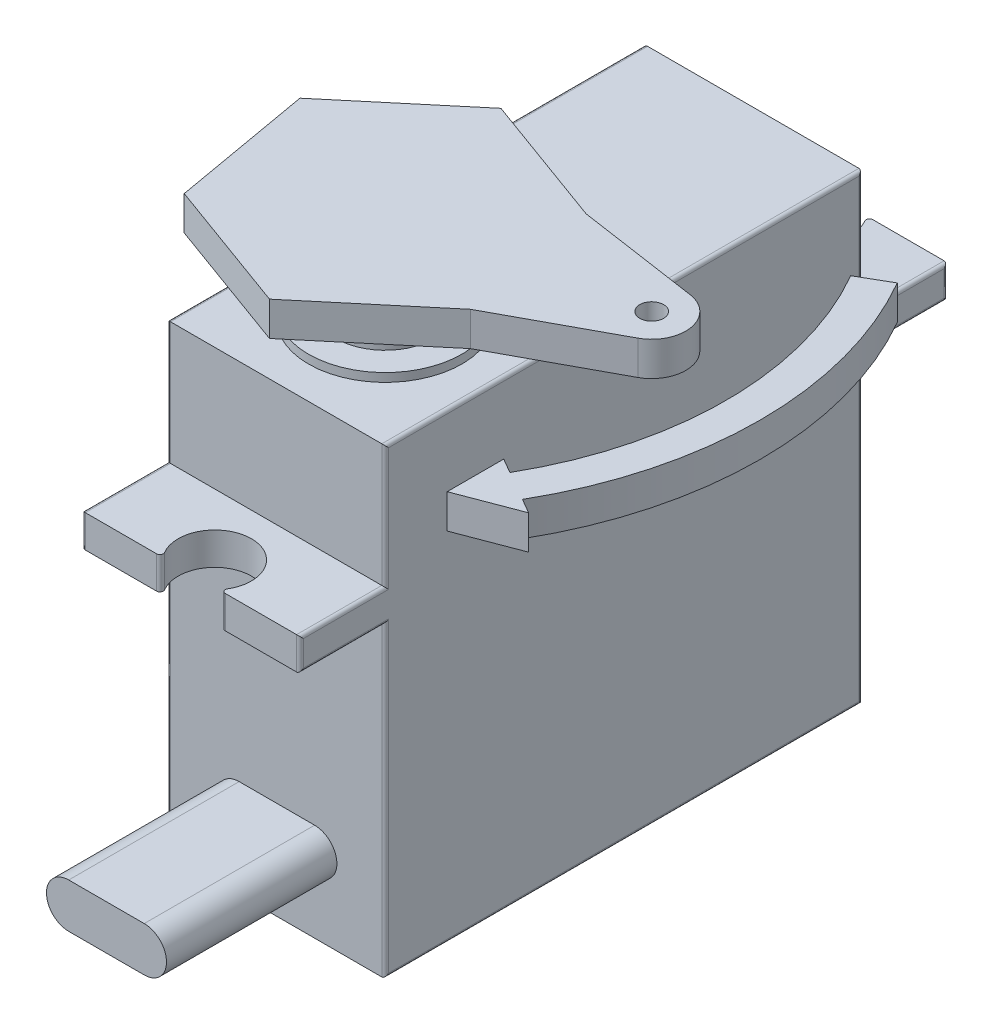
SolidWorks part; units mm, degrees
ref_plane "前视基准面" through (0, 0, 0) normal (0, 0, 1) x (1, 0, 0)
ref_plane "上视基准面" through (0, 0, 0) normal (0, 1, 0) x (1, 0, 0)
ref_plane "右视基准面" through (0, 0, 0) normal (1, 0, 0) x (0, 0, -1)
sketch "草图1" plane through (0, 0, 0) normal (0, 1, 0) x (1, 0, 0)
  line L0 (0, 13.4109) -> (0, 0) construction
  line L1 (-6.4, 14) -> (6.4, 14)
  line L2 (-6.4, 14) -> (-6.4, -14)
  line L3 (-6.4, -14) -> (6.4, -14)
  line L4 (6.4, 14) -> (6.4, -14)
  line L5 (0, 0) -> (14.8797, 0) construction
  dimension "D1" = 12.8
  dimension "D2" = 28
extrude "凸台-拉伸1" add sketch "草图1" along normal blind 18
sketch "草图2" plane through (0, 18, 0) normal (0, 1, 0) x (1, 0, 0)
  line L1 (-6.4, 19) -> (-2.0205, 19)
  line L2 (-6.4, 19) -> (-6.4, -19)
  line L3 (-6.4, -19) -> (-2.0205, -19)
  line L4 (6.4, 19) -> (6.4, -19)
  line L5 (-6.4, 14) -> (-6.4, -14) construction
  line L6 (6.4, -14) -> (6.4, 14) construction
  line L7 (0, 0) -> (17.3915, 0) construction
  line L8 (0, 17.6) -> (0, 0) construction
  line L9 (2.0205, 19) -> (6.4, 19)
  line L10 (2.0205, -19) -> (6.4, -19)
  arc A0 (-1.8486, 18.6979) -> (1.8486, 18.6979) centre (0, 17.6) ccw
  arc A1 (1.8486, -18.6979) -> (-1.8486, -18.6979) centre (0, -17.6) ccw
  arc A2 (1.8486, 18.6979) -> (2.0205, 19) centre (2.0205, 18.8) cw
  arc A3 (-1.8486, 18.6979) -> (-2.0205, 19) centre (-2.0205, 18.8) ccw
  arc A4 (2.0205, -19) -> (1.8486, -18.6979) centre (2.0205, -18.8) cw
  arc A5 (-2.0205, -19) -> (-1.8486, -18.6979) centre (-2.0205, -18.8) ccw
  point P19 (1.6317, 19)
  dimension "D2" = 4.3
  dimension "D4" = 0.2
  dimension "D1" = 38
  dimension "D3" = 35.2
extrude "凸台-拉伸2" add sketch "草图2" along normal blind 1.9
sketch "草图3" plane through (0, 19.9, 0) normal (0, 1, 0) x (1, 0, 0)
  line L0 (-6.4, 19) -> (-6.4, -19) construction
  line L1 (-6.4, 14) -> (6.4, 14)
  line L2 (-6.4, 14) -> (-6.4, -14)
  line L3 (-6.4, -14) -> (6.4, -14)
  line L4 (6.4, 14) -> (6.4, -14)
  line L5 (6.4, -19) -> (6.4, 19) construction
  line L6 (0, 22.3446) -> (0, 0) construction
  line L7 (0, 0) -> (13.1076, 0) construction
  line L8 (6.4, 14) -> (-6.4, 14) construction
extrude "凸台-拉伸3" add sketch "草图3" along normal blind 7.2
sketch "草图4" plane through (0, 27.1, 0) normal (0, 1, 0) x (1, 0, 0)
  line L0 (0, -14) -> (0, -7.6) construction
  line L1 (-6.4, -14) -> (6.4, -14) construction
  line L2 (0, -7.6) -> (-6.4, -7.6) construction
  line L3 (-6.4, 14) -> (-6.4, -14) construction
  circle A0 centre (0, -7.6) radius 4.5
  dimension "D1" = 9
extrude "凸台-拉伸4" add sketch "草图4" along normal blind 0.5
sketch "草图5" plane through (0, 27.6, 0) normal (0, 1, 0) x (1, 0, 0)
  circle A0 centre (0, -7.6) radius 2.9
  dimension "D1" = 5.8
extrude "凸台-拉伸5" add sketch "草图5" along normal blind 3.9
fillet "圆角1" radius 0.2 24 edges at (6.4, 18.95, 19) (6.4, 27.1, 0) (6.4, 18.95, -19) (6.4, 0, 0) (-6.4, 18.95, -19) (-6.4, 27.1, 0) (-6.4, 18.95, 19) (-6.4, 0, 0)
sketch "草图6" plane through (0, 0, 14) normal (0, 0, 1) x (1, 0, 0)
  line L0 (-2.1721, 4.4375) -> (2.2581, 4.4375) construction
  line L1 (-2.1721, 5.7438) -> (2.2581, 5.7438)
  line L2 (-2.1721, 3.1311) -> (2.2581, 3.1311)
  arc A0 (-2.1721, 5.7438) -> (-2.1721, 3.1311) centre (-2.1721, 4.4375) ccw
  arc A1 (2.2581, 3.1311) -> (2.2581, 5.7438) centre (2.2581, 4.4375) ccw
  point P2 (0.043, 4.4375)
extrude "凸台-拉伸6" add sketch "草图6" along normal blind 10
ref_plane "基准面1" through (0, 31, 0) normal (0, 1, 0) x (1, 0, 0)
sketch "草图7" plane through (0, 31, 0) normal (0, 1, 0) x (1, 0, 0)
  line L0 (6.413, -2.2189) -> (13.5868, -3.2772)
  line L1 (0, -7.6) -> (19.5227, -7.6) construction
  line L2 (1.4537, -15.8444) -> (7.8667, -10.4632)
  line L3 (0, -7.6) -> (20.0256, -4.0689) construction
  line L4 (16.4545, -17.1) -> (16.4545, -20.4163)
  line L5 (16.4545, -20.4163) -> (19.9186, -19.1)
  line L6 (19.9186, -19.1) -> (19.0526, -18.6)
  line L7 (17.3205, 2.4) -> (19.0526, 3.4)
  line L8 (17.3205, -17.6) -> (16.4545, -17.1)
  line L9 (7.8667, -10.4632) -> (6.413, -2.2189) construction
  line L10 (6.413, -2.2189) -> (-1.4537, 0.6444)
  line L11 (-1.4537, 0.6444) -> (-7.8667, -4.7368)
  line L12 (-7.8667, -4.7368) -> (-6.413, -12.9811)
  line L13 (-6.413, -12.9811) -> (1.4537, -15.8444)
  line L15 (7.8667, -10.4632) -> (14.2459, -7.0152)
  circle A0 centre (0, -7.6) radius 7.25 construction
  arc A1 (14.2459, -7.0152) -> (13.5868, -3.2772) centre (13.2949, -5.2557) ccw
  circle A2 centre (13.2949, -5.2557) radius 0.7
  circle A3 centre (0, -7.6) radius 13.5 construction
  arc A4 (17.3205, -17.6) -> (17.3205, 2.4) centre (0, -7.6) ccw
  arc A5 (19.0526, -18.6) -> (19.0526, 3.4) centre (0, -7.6) ccw
  circle A6 centre (0, -7.6) radius 22 construction
  circle A7 centre (0, -7.6) radius 20 construction
  dimension "D1" = 14.5
  dimension "D2" = 4
  dimension "D3" = 1.4
  dimension "D4" = 27
  dimension "D7" = 20
  dimension "D5" = 10
  dimension "D8" = 1
  dimension "D9" = 30
  dimension "D6" = 2
extrude "凸台-拉伸7" add sketch "草图7" along normal blind 2
